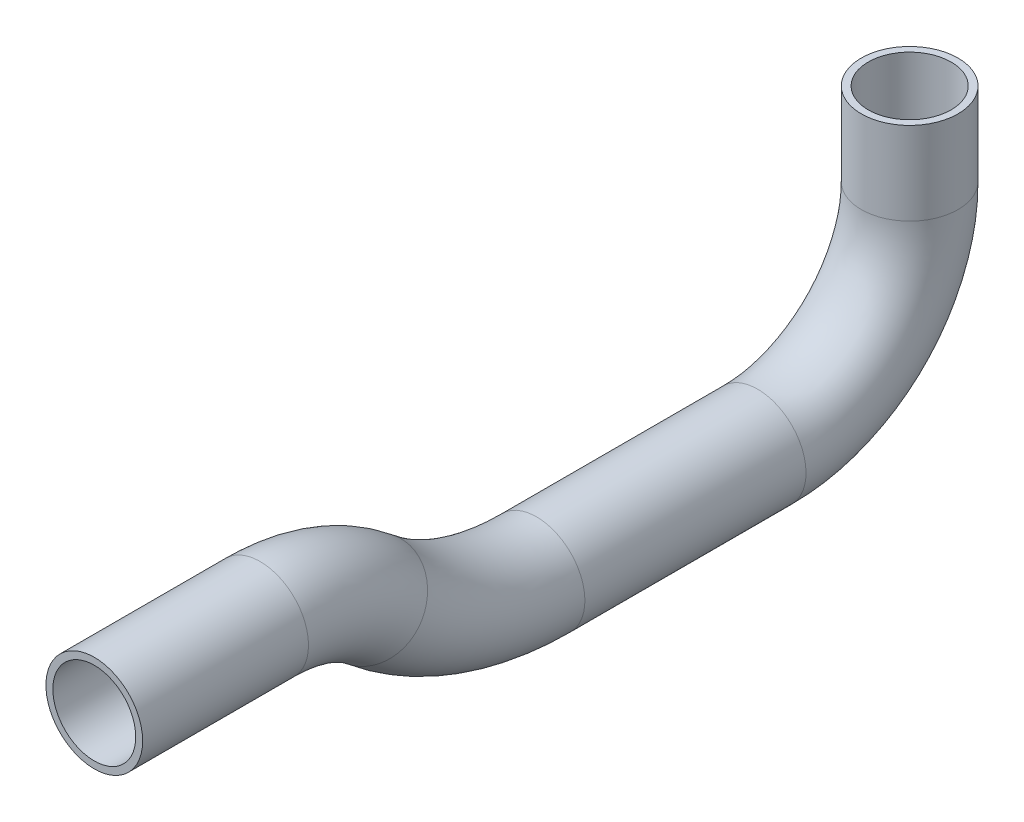
SolidWorks part; units mm, degrees
material "Copper"
ref_plane "Front Plane" through (0, 0, 0) normal (0, 0, 1) x (1, 0, 0)
ref_plane "Top Plane" through (0, 0, 0) normal (0, 1, 0) x (1, 0, 0)
ref_plane "Right Plane" through (0, 0, 0) normal (1, 0, 0) x (0, 0, -1)
sketch "Sketch6" plane through (0, 0, 0) normal (1, 0, 0) x (0, 0, -1)
  line L0 (0, 0) -> (12, 0)
  line L1 (0, -7.2) -> (62.5, -7.2) construction
  line L2 (62.5, -7.2) -> (62.5, 9.8) construction
  line L3 (32, -7.2) -> (48, -7.2)
  line L4 (59, 9.8) -> (59, 3.8)
  arc A0 (12, 0) -> (19.9674, -2.8683) centre (12, -12.5) cw
  arc A1 (19.9674, -2.8683) -> (32, -7.2) centre (32, 11.6778) ccw
  arc A2 (48, -7.2) -> (59, 3.8) centre (48, 3.8) ccw
  dimension "D2" = 32
  dimension "D3" = 12.5
  dimension "D7" = 11
  dimension "D1" = 12
  dimension "D4" = 17
  dimension "D5" = 7.2
  dimension "D6" = 62.5
  dimension "D8" = 3.5
sketch "Sketch7" plane through (0, 0, 0) normal (0, 0, 1) x (1, 0, 0)
  circle A0 centre (0, 0) radius 3
  circle A1 centre (0, 0) radius 3.5
  dimension "D1" = 7
  dimension "D2" = 6
sweep "Sweep3" add profiles "Sketch7" path "Sketch6"
